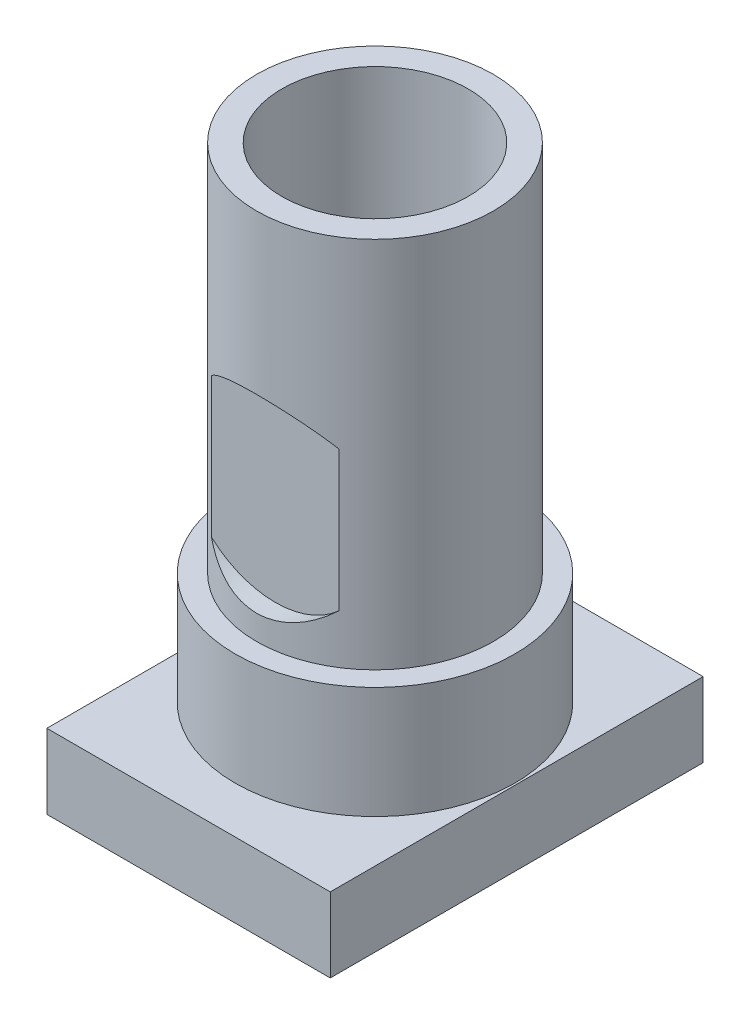
SolidWorks part; units mm, degrees
ref_plane "Front" through (0, 0, 0) normal (0, 0, 1) x (1, 0, 0)
ref_plane "Top" through (0, 0, 0) normal (0, 1, 0) x (1, 0, 0)
ref_plane "Right" through (0, 0, 0) normal (1, 0, 0) x (0, 0, -1)
sketch "Esquisse1" plane through (0, 0, 0) normal (0, 1, 0) x (1, 0, 0)
  line L1 (-3.8, 5) -> (3.8, 5)
  line L2 (-3.8, 5) -> (-3.8, -5)
  line L3 (-3.8, -5) -> (3.8, -5)
  line L4 (3.8, 5) -> (3.8, -5)
  line L5 (-3.8, 5) -> (3.8, -5) construction
  line L6 (-3.8, -5) -> (3.8, 5) construction
  point P0 (0, 0)
  dimension "D1" = 7.6
  dimension "D2" = 10
extrude "Boss.-Extru.1" add sketch "Esquisse1" along normal blind 2
sketch "Esquisse2" plane through (0, 2, 0) normal (0, 1, 0) x (1, 0, 0)
  circle A0 centre (0, 0) radius 3.75
  circle A1 centre (0, 0) radius 2.5
  dimension "D1" = 5
  dimension "D2" = 7.5
extrude "Boss.-Extru.2" add sketch "Esquisse2" along normal blind 3
sketch "Esquisse3" plane through (0, 5, 0) normal (0, 1, 0) x (1, 0, 0)
  circle A0 centre (0, 0) radius 2.5
  circle A1 centre (0, 0) radius 3.175
  dimension "D1" = 5
  dimension "D2" = 6.35
extrude "Boss.-Extru.3" add sketch "Esquisse3" along normal blind 10
sketch "Esquisse4" plane through (0, 2, 0) normal (0, 1, 0) x (1, 0, 0)
  circle A0 centre (0, 0) radius 1.325
  dimension "D1" = 2.65
extrude "Enlèv. mat.-Extru.1" cut sketch "Esquisse4" against normal through all
ref_plane "Plan1" through (0, 0, 3.175) normal (0, 0, 1) x (1, 0, 0)
sketch "Esquisse6" plane through (0, 0, 3.175) normal (0, 0, 1) x (1, 0, 0)
  line L0 (3.75, 5) -> (-3.75, 5) construction
  circle A0 centre (0, 8.2) radius 2.54
  dimension "D1" = 5.08
  dimension "D2" = 3.2
extrude "Enlèv. mat.-Extru.3" cut sketch "Esquisse6" against normal blind 0.5
